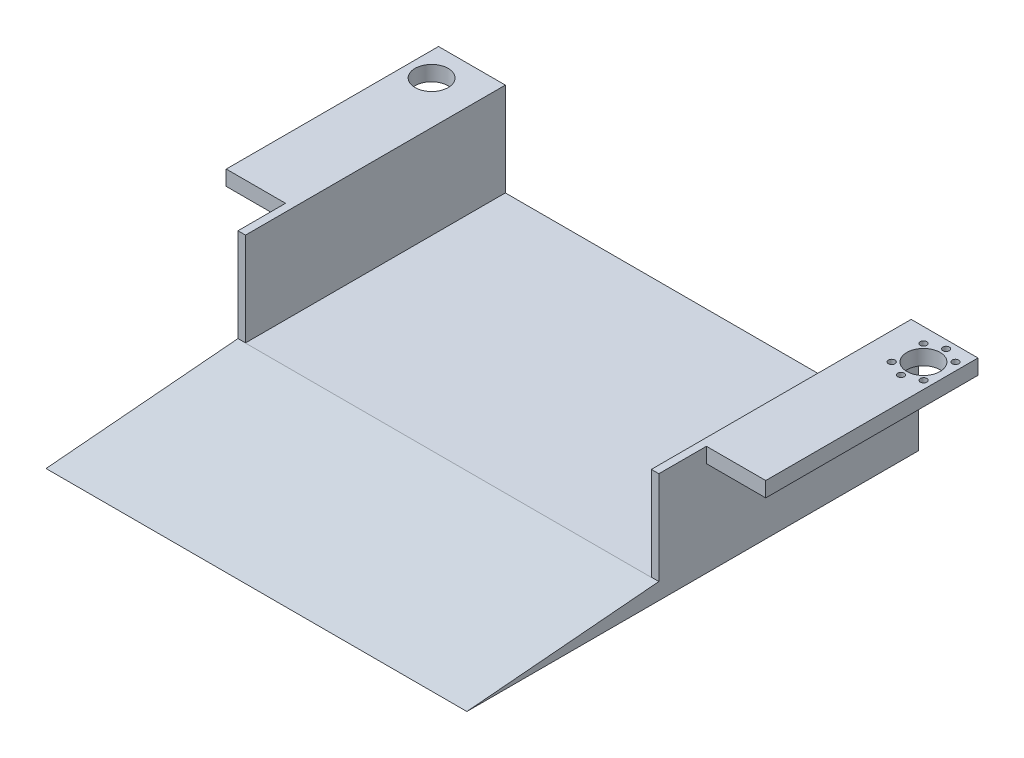
SolidWorks part; units mm, degrees
ref_plane "Front Plane" through (0, 0, 0) normal (0, 0, 1) x (1, 0, 0)
ref_plane "Top Plane" through (0, 0, 0) normal (0, 1, 0) x (1, 0, 0)
ref_plane "Right Plane" through (0, 0, 0) normal (1, 0, 0) x (0, 0, -1)
sketch "Sketch1" plane through (0, 0, 0) normal (0, 1, 0) x (1, 0, 0)
  line L1 (0, 0) -> (454.914, 0)
  line L2 (0, 0) -> (0, 381)
  line L3 (0, 381) -> (454.914, 381)
  line L4 (454.914, 0) -> (454.914, 381)
  dimension "D1" = 454.914
  dimension "D2" = 381
extrude "Boss-Extrude1" add sketch "Sketch1" along normal blind 92.6973
sketch "Sketch3" plane through (0, 92.6973, 0) normal (0, 1, 0) x (1, 0, 0)
  line L1 (454.914, 0) -> (404.9014, 0)
  line L2 (454.914, 0) -> (454.914, 202.0062)
  line L3 (454.914, 202.0062) -> (404.9014, 202.0062)
  line L4 (404.9014, 0) -> (404.9014, 202.0062)
  line L5 (0, 0) -> (50.0126, 0)
  line L6 (0, 0) -> (0, 202.0062)
  line L7 (0, 202.0062) -> (50.0126, 202.0062)
  line L8 (50.0126, 0) -> (50.0126, 202.0062)
  dimension "D1" = 202.0062
  dimension "D2" = 50.0126
  dimension "D3" = 202.0062
  dimension "D4" = 50.0126
extrude "Cut-Extrude1" cut sketch "Sketch3" against normal through all
sketch "Sketch4" plane through (0, 92.6973, 0) normal (0, 1, 0) x (1, 0, 0)
  line L0 (454.914, 381) -> (0, 381) construction
  line L1 (0, 381) -> (0, 202.0062) construction
  line L2 (454.914, 202.0062) -> (454.914, 381) construction
  circle A0 centre (20.066, 355.092) radius 14
  circle A1 centre (434.848, 355.092) radius 14
  dimension "D1" = 28
  dimension "D4" = 28
  dimension "D5" = 20.066
  dimension "D6" = 25.908
  dimension "D2" = 25.908
  dimension "D3" = 20.066
extrude "Cut-Extrude2" cut sketch "Sketch4" against normal through all
sketch "Sketch5" plane through (0, 92.6973, 0) normal (0, 1, 0) x (1, 0, 0)
  line L0 (454.914, 381) -> (0, 381) construction
  line L1 (56.3626, 381) -> (398.5514, 381)
  line L2 (56.3626, 381) -> (56.3626, 0)
  line L3 (56.3626, 0) -> (398.5514, 0)
  line L4 (398.5514, 381) -> (398.5514, 0)
  line L5 (50.0126, 0) -> (404.9014, 0) construction
  line L6 (50.0126, 0) -> (50.0126, 202.0062) construction
  line L7 (404.9014, 202.0062) -> (404.9014, 0) construction
  dimension "D1" = 6.35
  dimension "D2" = 6.35
extrude "Cut-Extrude3" cut sketch "Sketch5" against normal blind 78.74
sketch "Sketch6" plane through (454.914, 0, 0) normal (1, 0, 0) x (0, 0, -1)
  line L0 (381, 92.6973) -> (381, 0) construction
  line L1 (202.0062, 0) -> (381, 0)
  line L2 (202.0062, 0) -> (202.0062, 79.9974)
  line L3 (202.0062, 79.9974) -> (381, 79.9974)
  line L4 (381, 0) -> (381, 79.9974)
  dimension "D1" = 79.9974
extrude "Cut-Extrude4" cut sketch "Sketch6" against normal blind 50.0126
sketch "Sketch7" plane through (0, 0, 0) normal (-1, 0, 0) x (0, 0, 1)
  line L0 (-202.0062, 0) -> (-202.0062, 92.6973) construction
  line L1 (-381, 0) -> (-202.0062, 0)
  line L2 (-381, 0) -> (-381, 79.9974)
  line L3 (-381, 79.9974) -> (-202.0062, 79.9974)
  line L4 (-202.0062, 0) -> (-202.0062, 79.9974)
  dimension "D1" = 79.9974
extrude "Cut-Extrude5" cut sketch "Sketch7" against normal blind 50.0126
sketch "Sketch10" plane through (404.9014, 0, 0) normal (1, 0, 0) x (0, 0, -1)
  line L0 (0, 0) -> (161.8995, 13.97)
  line L1 (202.0062, 92.6973) -> (0, 92.6973) construction
  line L3 (161.8995, 92.6973) -> (161.8995, 13.97)
  line L8 (161.8995, 92.6973) -> (0, 92.6973)
  line L9 (0, 92.6973) -> (0, 0)
extrude "Cut-Extrude6" cut sketch "Sketch10" against normal through all
sketch "Sketch11" plane through (0, 92.6973, 0) normal (0, 1, 0) x (1, 0, 0)
  line L0 (434.848, 385.1807) -> (434.848, 325.1677) construction
  line L1 (457.9437, 355.092) -> (408.0384, 355.092) construction
  line L2 (434.848, 355.1742) -> (453.5332, 373.8594) construction
  line L3 (434.848, 355.1742) -> (419.9379, 370.0843) construction
  line L4 (434.848, 355.1742) -> (452.7645, 337.2577) construction
  line L5 (434.848, 355.1742) -> (417.2384, 337.5646) construction
  circle A1 centre (434.848, 374.1742) radius 2.75
  circle A2 centre (448.283, 368.6092) radius 2.75
  circle A3 centre (421.413, 368.6092) radius 2.75
  circle A4 centre (448.283, 341.7392) radius 2.75
  circle A5 centre (434.848, 336.1742) radius 2.75
  circle A6 centre (421.413, 341.7392) radius 2.75
  dimension "D2" = 45
  dimension "D5" = 5.5
  dimension "D6" = 5.5
  dimension "D7" = 5.5
  dimension "D8" = 5.5
  dimension "D9" = 5.5
  dimension "D10" = 5.5
  dimension "D3" = 45
  dimension "D4" = 45
extrude "Cut-Extrude7" cut sketch "Sketch11" against normal through all
